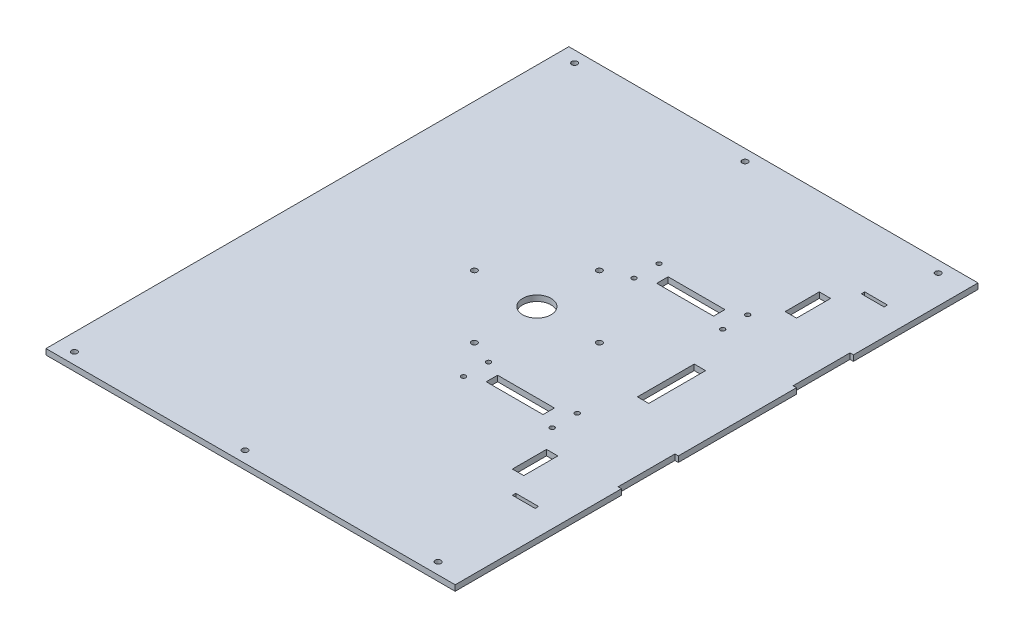
SolidWorks part; units mm, degrees
material "아크릴(내충격성)"
ref_plane "정면" through (0, 0, 0) normal (0, 0, 1) x (1, 0, 0)
ref_plane "윗면" through (0, 0, 0) normal (0, 1, 0) x (1, 0, 0)
ref_plane "우측면" through (0, 0, 0) normal (1, 0, 0) x (0, 0, -1)
sketch "스케치1" plane through (0, 0, 0) normal (0, 1, 0) x (1, 0, 0)
  line L0 (-113.0197, -185) -> (116.1534, -185) construction
  line L1 (-50, 175) -> (0, 175)
  line L2 (-100, 175) -> (-100, -175)
  line L3 (-50, -175) -> (0, -175)
  line L4 (100, 175) -> (100, -175)
  line L5 (-100, 175) -> (100, -175) construction
  line L6 (-100, -175) -> (100, 175) construction
  line L7 (-242.4397, 0) -> (206.3887, 0) construction
  line L8 (-100, -175) -> (-100, -185)
  line L9 (-100, -185) -> (-50, -185)
  line L10 (-50, -185) -> (-50, -175)
  line L11 (0, -175) -> (0, -185)
  line L12 (0, -185) -> (50, -185)
  line L13 (50, -185) -> (50, -175)
  line L14 (50, 185) -> (50, 175)
  line L15 (0, 185) -> (50, 185)
  line L16 (0, 175) -> (0, 185)
  line L17 (-50, 185) -> (-50, 175)
  line L18 (-100, 185) -> (-50, 185)
  line L19 (-100, 175) -> (-100, 185)
  line L20 (50, 175) -> (100, 175)
  line L21 (50, -175) -> (100, -175)
  point P0 (0, 0)
  dimension "D1" = 350
  dimension "D2" = 200
  dimension "D3" = 10
  dimension "D4" = 50
  dimension "D5" = 50
  dimension "D6" = 50
extrude "보스-돌출1" add sketch "스케치1" along normal blind 5
sketch "스케치2" plane through (0, 5, 0) normal (0, 1, 0) x (1, 0, 0)
  line L0 (0, 155) -> (0, -155) construction
  line L1 (0, -155) -> (100, -155) construction
  line L2 (100, -175) -> (100, 175) construction
  line L3 (0, 155) -> (100, 155) construction
  line L4 (100, 175) -> (50, 175) construction
  line L5 (50, -175) -> (100, -175) construction
  line L18 (124.0343, 0) -> (-128.3419, 0) construction
  line L23 (80, 155) -> (60, 155)
  line L24 (80, 155) -> (80, 152)
  line L25 (80, 152) -> (60, 152)
  line L26 (60, 155) -> (60, 152)
  line L31 (80, -152) -> (60, -152)
  line L32 (60, -155) -> (60, -152)
  line L33 (80, -155) -> (60, -155)
  line L34 (80, -155) -> (80, -152)
  line L39 (40, 155) -> (40, -155) construction
  line L40 (40, 105) -> (50, 105)
  line L41 (40, 135) -> (50, 135)
  line L42 (40, 135) -> (40, 105)
  line L43 (40, -135) -> (50, -135)
  line L44 (50, 135) -> (50, 105)
  line L45 (40, -105) -> (50, -105)
  line L46 (40, 25) -> (50, 25)
  line L47 (40, -25) -> (50, -25)
  line L48 (50, 25) -> (50, -25)
  line L49 (40, 25) -> (40, -25)
  line L50 (40, -105) -> (40, -135)
  line L51 (50, -105) -> (50, -135)
  dimension "D1" = 20
  dimension "D2" = 20
  dimension "D3" = 20
  dimension "D4" = 20
  dimension "D6" = 10
  dimension "D7" = 20
  dimension "D8" = 3
  dimension "D9" = 20
  dimension "D10" = 30
  dimension "D11" = 25
  dimension "D12" = 50
  dimension "D13" = 20
  dimension "D5" = 60
  dimension "D14" = 30
extrude "컷-돌출1" cut sketch "스케치2" against normal through all
sketch "스케치3" plane through (0, 5, 0) normal (0, 1, 0) x (1, 0, 0)
  line L0 (0, 0) -> (-919.3874, 0) construction
  line L1 (-100, 185) -> (-100, -185) construction
  line L2 (-540.91, 50) -> (-225, 50)
  line L4 (-540.91, -50) -> (-225, -50)
  line L6 (-540.91, 50) -> (-100, -50) construction
  line L7 (-540.91, -50) -> (-100, 50) construction
  line L8 (-540.91, 50) -> (-540.91, 185)
  line L9 (-590.91, -185) -> (-540.91, -185)
  line L10 (-590.91, -185) -> (-590.91, 185)
  line L11 (-590.91, 185) -> (-540.91, 185)
  line L12 (-540.91, -185) -> (-540.91, -50)
  line L13 (-590.91, -185) -> (-540.91, 185) construction
  line L14 (-590.91, 185) -> (-540.91, -185) construction
  line L15 (-50, 175) -> (-100, 175) construction
  line L16 (-50, -175) -> (-100, -175) construction
  line L19 (-100, 50) -> (-100, -50)
  line L20 (-225, 50) -> (-100, 50)
  line L21 (-225, -50) -> (-100, -50)
  point P3 (-320.455, 0)
  point P10 (-565.91, 0)
  dimension "D1" = 370
  dimension "D2" = 50
  dimension "D3" = 440.91
  dimension "D4" = 100
extrude "보스-돌출2" add sketch "스케치3" against normal blind 5
sketch "스케치4" plane through (0, 5, 0) normal (0, 1, 0) x (1, 0, 0)
  line L0 (-590.91, 185) -> (-590.91, -185) construction
  line L1 (-540.91, 185) -> (-590.91, 185) construction
  line L2 (-590.91, -185) -> (-540.91, -185) construction
  circle A0 centre (-578.91, 145) radius 2
  circle A1 centre (-578.91, 95) radius 2
  circle A2 centre (-566.91, 145) radius 2
  circle A3 centre (-566.91, 95) radius 2
  circle A4 centre (-578.91, -145) radius 2
  circle A5 centre (-578.91, -95) radius 2
  circle A6 centre (-566.91, -95) radius 2
  circle A7 centre (-566.91, -145) radius 2
  dimension "12" = 12
  dimension "D2" = 12
  dimension "D3" = 12
  dimension "D4" = 12
  dimension "D5" = 50
  dimension "D6" = 40
  dimension "D7" = 12
  dimension "D8" = 12
  dimension "D9" = 12
  dimension "D10" = 12
  dimension "D11" = 50
  dimension "D12" = 40
extrude "컷-돌출2" cut sketch "스케치4" against normal through all
sketch "스케치6" plane through (0, 5, 0) normal (0, 1, 0) x (1, 0, 0)
  line L0 (80, 152) -> (100, 152) construction
  line L1 (100, -175) -> (100, 175) construction
  line L2 (80, -152) -> (100, -152) construction
  line L3 (100, -102) -> (103, -102)
  line L4 (100, 152) -> (103, 152)
  line L5 (100, 152) -> (100, 102)
  line L6 (100, -152) -> (103, -152)
  line L7 (103, 152) -> (103, 102)
  line L8 (100, -52) -> (103, -52)
  line L9 (103, -102) -> (103, -152)
  line L10 (100, 52) -> (103, 52)
  line L11 (100, 102) -> (103, 102)
  line L12 (100, -102) -> (100, -152)
  line L13 (103, 52) -> (103, -52)
  line L14 (100, 52) -> (100, -52)
  dimension "D1" = 3
  dimension "D2" = 50
  dimension "D3" = 50
  dimension "D5" = 50
extrude "보스-돌출3" add sketch "스케치6" against normal blind 5
sketch "스케치7" plane through (0, 5, 0) normal (0, 1, 0) x (1, 0, 0)
  line L0 (-540.91, -185) -> (-537.91, -185)
  line L1 (-566.91, 95) -> (-100, 95) construction
  line L2 (-100, 185) -> (-100, 50) construction
  line L3 (-566.91, -95) -> (-100, -95) construction
  line L4 (-100, -50) -> (-100, -185) construction
  line L5 (-537.91, 92) -> (-495.91, 50)
  line L7 (-100, 50) -> (-540.91, 50) construction
  line L8 (-537.91, -92) -> (-495.91, -50)
  line L9 (-540.91, -50) -> (-100, -50) construction
  line L10 (-100, 95) -> (-145, 50)
  line L11 (-100, -95) -> (-145, -50)
  line L13 (-540.91, 50) -> (-495.91, 50)
  line L14 (-495.91, -50) -> (-540.91, -50)
  line L16 (-145, 50) -> (-100, 50)
  line L17 (-100, 50) -> (-100, 95)
  line L18 (-145, -50) -> (-100, -50)
  line L19 (-100, -50) -> (-100, -95)
  line L20 (-537.91, -185) -> (-537.91, -92)
  line L21 (-540.91, 185) -> (-537.91, 185)
  line L22 (-537.91, 92) -> (-537.91, 185)
  line L26 (-540.91, 185) -> (-540.91, 50)
  line L27 (-540.91, -50) -> (-540.91, -185)
  dimension "D1" = 3
extrude "보스-돌출4" add sketch "스케치7" against normal blind 5
sketch "스케치8" plane through (0, 5, 0) normal (0, 1, 0) x (1, 0, 0)
  line L0 (103, 0) -> (-190.2482, 0) construction
  line L1 (103, -52) -> (103, 52) construction
  line L2 (-58, 80) -> (32, 80) construction
  line L3 (40, 135) -> (40, 105) construction
  line L4 (-52, 90.1952) -> (-52, 60.3071) construction
  line L5 (-38, 80) -> (12, 80)
  line L6 (-38, 80) -> (-38, 70)
  line L7 (-38, 70) -> (12, 70)
  line L8 (12, 80) -> (12, 70)
  line L9 (-58, 70) -> (32, 70) construction
  line L10 (26, 89.397) -> (26, 62.9791) construction
  line L11 (-63, 86) -> (27, 86) construction
  line L12 (-58, 64) -> (32, 64) construction
  line L13 (12, -80) -> (12, -70)
  line L14 (-38, -80) -> (12, -80)
  line L15 (-38, -70) -> (12, -70)
  line L16 (-38, -80) -> (-38, -70)
  circle A0 centre (-52, 86) radius 2
  circle A1 centre (-52, 64) radius 2
  circle A2 centre (26, 86) radius 2
  circle A3 centre (26, 64) radius 2
  circle A4 centre (-52, -86) radius 2
  circle A5 centre (-52, -64) radius 2
  circle A6 centre (26, -64) radius 2
  circle A7 centre (26, -86) radius 2
  dimension "D1" = 80
  dimension "D2" = 90
  dimension "D3" = 8
  dimension "D4" = 20
  dimension "D5" = 20
  dimension "D6" = 10
  dimension "D7" = 6
  dimension "D8" = 6
  dimension "D9" = 6
  dimension "D10" = 6
extrude "컷-돌출3" cut sketch "스케치8" against normal through all
sketch "스케치9" plane through (0, 5, 0) normal (0, 1, 0) x (1, 0, 0)
  line L0 (-590.91, 0) -> (-107.718, 0) construction
  line L1 (-590.91, 185) -> (-590.91, -185) construction
  line L2 (-537.91, 92) -> (-537.91, -92) construction
  line L3 (-537.91, 30) -> (-107.718, 30) construction
  line L4 (-437.91, 60.414) -> (-437.91, 0) construction
  line L5 (-235.58, 0) -> (-235.58, 62.7869) construction
  line L6 (-185.58, 0) -> (-185.58, 62.7869) construction
  circle A0 centre (-437.91, 30) radius 2
  circle A1 centre (-235.58, 30) radius 2
  circle A2 centre (-185.58, 30) radius 2
  circle A3 centre (-185.58, -30) radius 2
  circle A4 centre (-235.58, -30) radius 2
  circle A5 centre (-437.91, -30) radius 2
  dimension "D1" = 30
  dimension "D2" = 100
  dimension "D3" = 50
  dimension "D4" = 202.33
extrude "컷-돌출4" cut sketch "스케치9" against normal through all
sketch "스케치10" plane through (0, 5, 0) normal (0, 1, 0) x (1, 0, 0)
  line L1 (-13, 0) -> (-73, 0)
  line L2 (-38, 70) -> (12, 70) construction
  line L3 (-38, 70) -> (12, 70)
  circle A1 centre (-73, 0) radius 7.5
  circle A2 centre (-73, 0) radius 60
  dimension "D1" = 15
  dimension "D2" = 120
extrude "컷-돌출5" cut sketch "스케치10" against normal through all
sketch "스케치11" plane through (0, 5, 0) normal (0, 1, 0) x (1, 0, 0)
  line L1 (103, 211.6565) -> (103, -248.3435)
  line L2 (-257, 211.6565) -> (-257, -248.3435)
  line L3 (103, -248.3435) -> (-257, -248.3435)
  line L4 (-257, 211.6565) -> (103, 211.6565)
  line L45 (-145, -50) -> (-100, -95)
  line L46 (-100, -95) -> (-100, -185)
  line L47 (-100, -185) -> (-50, -185)
  line L48 (-50, -185) -> (-50, -175)
  line L49 (-50, -175) -> (0, -175)
  line L50 (0, -175) -> (0, -185)
  line L51 (0, -185) -> (50, -185)
  line L52 (50, -185) -> (50, -175)
  line L53 (50, -175) -> (100, -175)
  line L54 (100, -175) -> (100, -152)
  line L55 (100, -152) -> (103, -152)
  line L56 (103, -152) -> (103, -102)
  line L57 (103, -102) -> (100, -102)
  line L58 (100, -102) -> (100, -52)
  line L59 (100, -52) -> (103, -52)
  line L60 (103, -52) -> (103, 52)
  line L61 (103, 52) -> (100, 52)
  line L62 (100, 52) -> (100, 102)
  line L63 (100, 102) -> (103, 102)
  line L64 (103, 102) -> (103, 152)
  line L65 (103, 152) -> (100, 152)
  line L66 (100, 152) -> (100, 175)
  line L67 (100, 175) -> (50, 175)
  line L68 (50, 175) -> (50, 185)
  line L69 (50, 185) -> (0, 185)
  line L70 (0, 185) -> (0, 175)
  line L71 (0, 175) -> (-50, 175)
  line L72 (-50, 175) -> (-50, 185)
  line L73 (-50, 185) -> (-100, 185)
  line L74 (-100, 185) -> (-100, 95)
  line L75 (-100, 95) -> (-145, 50)
  line L76 (-145, 50) -> (-495.91, 50)
  line L77 (-495.91, 50) -> (-537.91, 92)
  line L78 (-537.91, 92) -> (-537.91, 185)
  line L79 (-537.91, 185) -> (-590.91, 185)
  line L80 (-590.91, 185) -> (-590.91, -185)
  line L81 (-590.91, -185) -> (-537.91, -185)
  line L82 (-537.91, -185) -> (-537.91, -92)
  line L83 (-537.91, -92) -> (-495.91, -50)
  line L84 (-495.91, -50) -> (-145, -50)
  line L85 (-145, -50) -> (-100, -95)
  line L86 (-100, -95) -> (-100, -185)
  line L87 (-100, -185) -> (-50, -185)
  line L88 (-50, -185) -> (-50, -175)
  line L89 (-50, -175) -> (0, -175)
  line L90 (0, -175) -> (0, -185)
  line L91 (0, -185) -> (50, -185)
  line L92 (50, -185) -> (50, -175)
  line L93 (50, -175) -> (100, -175)
  line L94 (100, -175) -> (100, -152)
  line L95 (100, -152) -> (103, -152)
  line L96 (103, -152) -> (103, -102)
  line L97 (103, -102) -> (100, -102)
  line L98 (100, -102) -> (100, -52)
  line L99 (100, -52) -> (103, -52)
  line L100 (103, -52) -> (103, 52)
  line L101 (103, 52) -> (100, 52)
  line L102 (100, 52) -> (100, 102)
  line L103 (100, 102) -> (103, 102)
  line L104 (103, 102) -> (103, 152)
  line L105 (103, 152) -> (100, 152)
  line L106 (100, 152) -> (100, 175)
  line L107 (100, 175) -> (50, 175)
  line L108 (50, 175) -> (50, 185)
  line L109 (50, 185) -> (0, 185)
  line L110 (0, 185) -> (0, 175)
  line L111 (0, 175) -> (-50, 175)
  line L112 (-50, 175) -> (-50, 185)
  line L113 (-50, 185) -> (-100, 185)
  line L114 (-100, 185) -> (-100, 95)
  line L115 (-100, 95) -> (-145, 50)
  line L116 (-145, 50) -> (-495.91, 50)
  line L117 (-495.91, 50) -> (-537.91, 92)
  line L118 (-537.91, 92) -> (-537.91, 185)
  line L119 (-537.91, 185) -> (-590.91, 185)
  line L120 (-590.91, 185) -> (-590.91, -185)
  line L121 (-590.91, -185) -> (-537.91, -185)
  line L122 (-537.91, -185) -> (-537.91, -92)
  line L123 (-537.91, -92) -> (-495.91, -50)
  line L124 (-495.91, -50) -> (-145, -50)
  dimension "D1" = 0
extrude "보스-돌출5" add sketch "스케치11" against normal blind 5 contours L124 L2 L3 L1 L95 L94 L93 L92 L91 L90 L89 L88 L87 L86 L85 | L116 L115 L114 L113 L112 L111 L110 L109 L108 L107 L106 L105 L1 L4 L2
sketch "스케치12" plane through (0, 5, 0) normal (0, 1, 0) x (1, 0, 0)
  line L0 (-257, 211.6565) -> (-257, -248.3435)
  line L1 (-257, 211.6565) -> (-627.4363, 211.6565)
  line L2 (-257, -248.3435) -> (-627.4363, -248.3435)
  line L3 (-627.4363, -248.3435) -> (-627.4363, 211.6565)
extrude "컷-돌출6" cut sketch "스케치12" against normal through all
sketch "스케치15" plane through (0, 5, 0) normal (0, 1, 0) x (1, 0, 0)
  circle A2 centre (-73.0502, -55.4165) radius 2.5
  circle A3 centre (-128.0502, -0.4165) radius 2.5
  circle A4 centre (-73.0502, 54.5835) radius 2.5
  circle A5 centre (-18.0502, -0.4165) radius 2.5
  circle A6 centre (-73.0502, -0.4165) radius 12.5
  circle A8 centre (-242, 201.6565) radius 2.5
  circle A9 centre (-92, 201.6565) radius 2.5
  circle A10 centre (78, 201.6565) radius 2.5
  circle A11 centre (78, -238.3435) radius 2.5
  circle A12 centre (-92, -238.3435) radius 2.5
  circle A13 centre (-242, -238.3435) radius 2.5
  point P12 (-73.0502, -0.4165)
  dimension "D1" = 25
extrude "컷-돌출7" cut sketch "스케치15" against normal through all
sketch "스케치16" plane through (0, 5, 0) normal (0, 1, 0) x (1, 0, 0)
  circle A0 centre (-185.58, -30) radius 2 construction
  circle A1 centre (-235.58, -30) radius 2 construction
  circle A2 centre (-185.58, 30) radius 2 construction
  circle A3 centre (-235.58, 30) radius 2 construction
  circle A4 centre (-185.58, -30) radius 2
  circle A5 centre (-235.58, -30) radius 2
  circle A6 centre (-185.58, 30) radius 2
  circle A7 centre (-235.58, 30) radius 2
extrude "보스-돌출6" add sketch "스케치16" against normal blind 5
